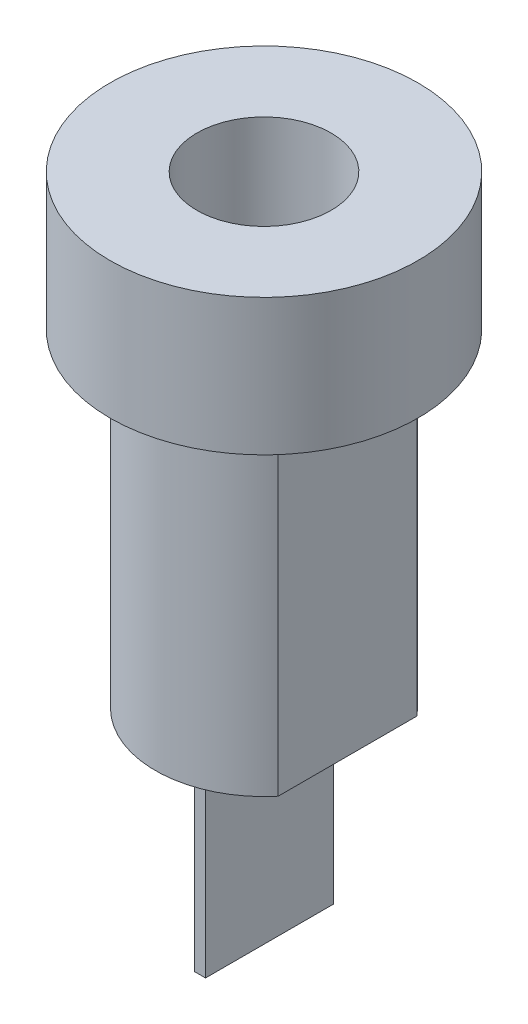
SolidWorks part; units mm, degrees
ref_plane "Front Plane" through (0, 0, 0) normal (0, 0, 1) x (1, 0, 0)
ref_plane "Top Plane" through (0, 0, 0) normal (0, 1, 0) x (1, 0, 0)
ref_plane "Right Plane" through (0, 0, 0) normal (1, 0, 0) x (0, 0, -1)
sketch "Sketch1" plane through (0, 0, 0) normal (1, 0, 0) x (0, 0, -1)
  line L0 (-2.41, 16.68) -> (-5.53, 16.68)
  line L1 (-5.53, 16.68) -> (-5.53, 11.78)
  line L2 (-5.53, 11.78) -> (-3.9, 11.78)
  line L3 (-3.9, 11.78) -> (-3.9, 0)
  line L4 (-3.9, 0) -> (0, 0)
  line L5 (0, 0) -> (0, 11.78)
  line L6 (0, 0) -> (0, 26.1429) construction
  line L7 (-2.41, 16.68) -> (-2.41, 11.78)
  line L8 (-2.41, 11.78) -> (0, 11.78)
  dimension "D1" = 11.06
  dimension "D2" = 7.8
  dimension "D3" = 11.78
  dimension "D4" = 16.68
  dimension "D5" = 4.82
revolve "Revolve1" add sketch "Sketch1" angle 360 about L6
sketch "Sketch2" plane through (0, 0, 0) normal (0, -1, 0) x (1, 0, 0)
  line L0 (3, -2.492) -> (3, 2.492)
  line L1 (-3, 2.492) -> (-3, -2.492)
  arc A0 (-3, 2.492) -> (-3, -2.492) centre (0, 0) ccw
  circle A1 centre (0, 0) radius 3.9
  arc A2 (3, -2.492) -> (3, 2.492) centre (0, 0) ccw
  dimension "D2" = 6
  dimension "D1" = 0
extrude "Cut-Extrude1" cut sketch "Sketch2" against normal up to surface (11.78 mm away) up to face at (0, 11.78, -3.9)
sketch "Sketch3" plane through (0, 0, 0) normal (0, -1, 0) x (1, 0, 0)
  line L1 (-0.2, -2.3) -> (0.2, -2.3)
  line L2 (-0.2, -2.3) -> (-0.2, 2.3)
  line L3 (-0.2, 2.3) -> (0.2, 2.3)
  line L4 (0.2, -2.3) -> (0.2, 2.3)
  line L5 (-0.2, -2.3) -> (0.2, 2.3) construction
  line L6 (-0.2, 2.3) -> (0.2, -2.3) construction
  point P0 (0, 0)
  dimension "D1" = 0.4
  dimension "D2" = 4.6
extrude "Boss-Extrude1" add sketch "Sketch3" along normal blind 7.15
